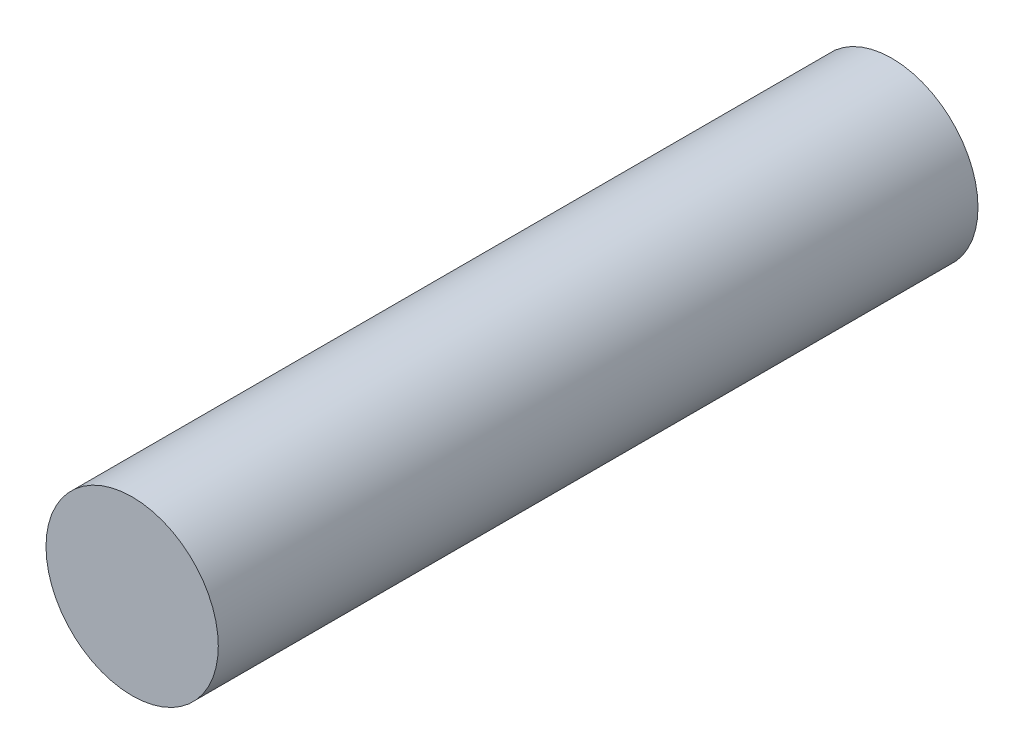
SolidWorks part; units mm, degrees
ref_plane "Front Plane" through (0, 0, 0) normal (0, 0, 1) x (1, 0, 0)
ref_plane "Top Plane" through (0, 0, 0) normal (0, 1, 0) x (1, 0, 0)
ref_plane "Right Plane" through (0, 0, 0) normal (1, 0, 0) x (0, 0, -1)
sketch "Sketch2" plane through (0, 0, 0) normal (0, 0, 1) x (1, 0, 0)
  circle A0 centre (0, 0) radius 5.5
  dimension "D1" = 11
extrude "Boss-Extrude1" add sketch "Sketch2" along normal blind 48.5
